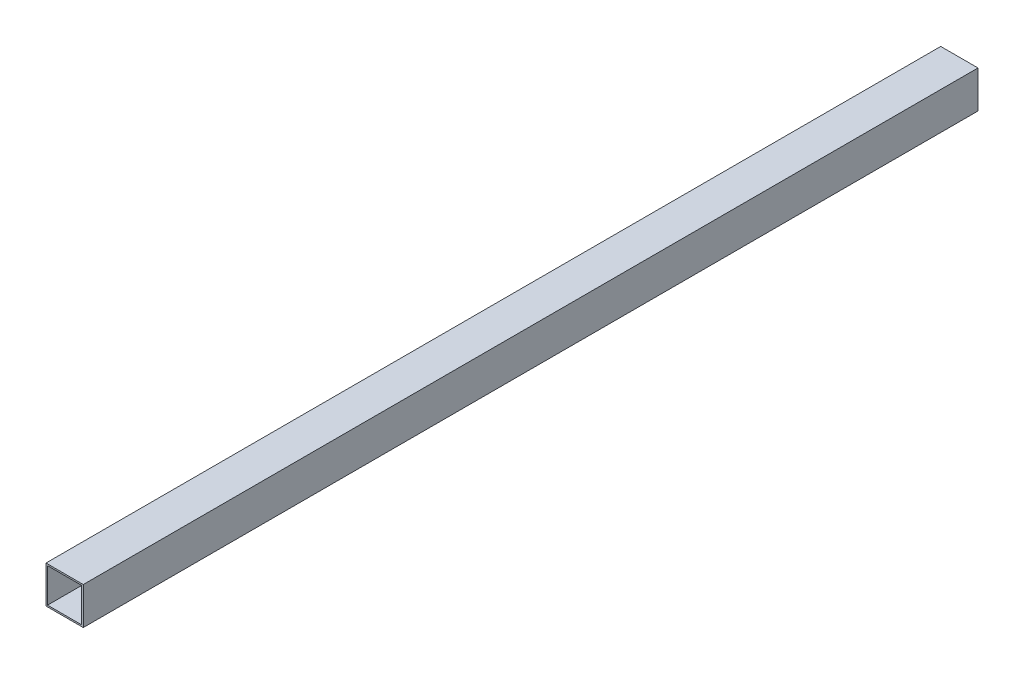
SolidWorks part; units mm, degrees
material "Plain Carbon Steel"
ref_plane "Front Plane" through (0, 0, 0) normal (0, 0, 1) x (1, 0, 0)
ref_plane "Top Plane" through (0, 0, 0) normal (0, 1, 0) x (1, 0, 0)
ref_plane "Right Plane" through (0, 0, 0) normal (1, 0, 0) x (0, 0, -1)
sketch "Sketch2" plane through (0, 0, 0) normal (0, 0, 1) x (1, 0, 0)
  line L0 (0, 19.05) -> (1.5875, 19.05) construction
  line L1 (0, 0) -> (38.1, 0)
  line L2 (0, 0) -> (0, 38.1)
  line L3 (0, 38.1) -> (38.1, 38.1)
  line L4 (38.1, 0) -> (38.1, 38.1)
  line L5 (1.5875, 1.5875) -> (36.5125, 1.5875)
  line L6 (1.5875, 1.5875) -> (1.5875, 36.5125)
  line L7 (1.5875, 36.5125) -> (36.5125, 36.5125)
  line L8 (36.5125, 1.5875) -> (36.5125, 36.5125)
  line L9 (19.05, 36.5125) -> (19.05, 38.1) construction
  line L10 (36.5125, 19.05) -> (38.1, 19.05) construction
  line L11 (19.05, 0) -> (19.05, 1.5875) construction
  dimension "D1" = 38.1
  dimension "D2" = 1.5875
  dimension "D3" = 38.1
extrude "Boss-Extrude1" add sketch "Sketch2" along normal blind 914.4
